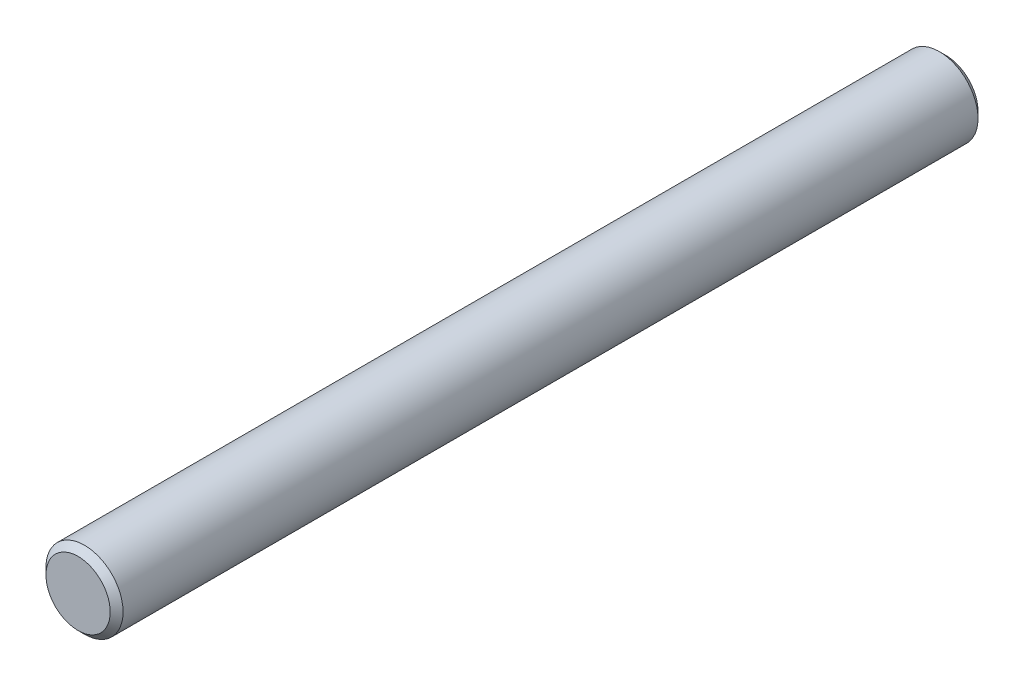
SolidWorks part; units mm, degrees
ref_plane "Спереди" through (0, 0, 0) normal (0, 0, 1) x (1, 0, 0)
ref_plane "Сверху" through (0, 0, 0) normal (0, 1, 0) x (1, 0, 0)
ref_plane "Справа" through (0, 0, 0) normal (1, 0, 0) x (0, 0, -1)
sketch "Эскиз3" plane through (0, 0, 0) normal (0, 0, 1) x (1, 0, 0)
  circle A0 centre (0, 0) radius 6
  dimension "D1" = 12
extrude "Бобышка-Вытянуть1" add sketch "Эскиз3" along normal mid plane 135
chamfer "Фаска1" distance 1 angle 45 2 edges at (6, 0, -67.5) (6, 0, 67.5)
